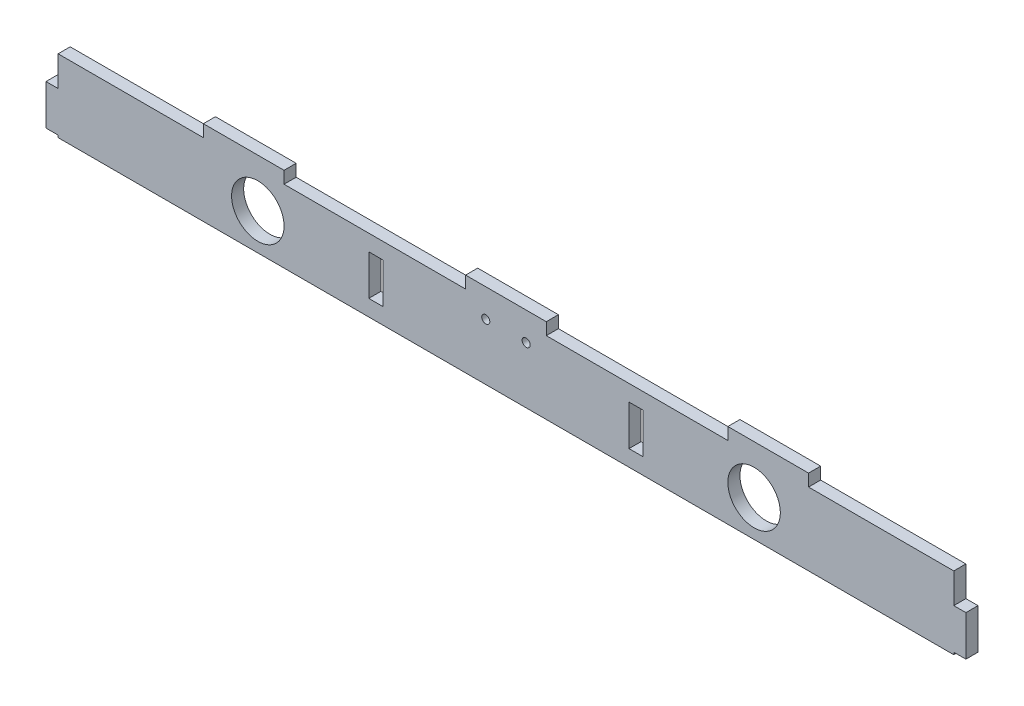
SolidWorks part; units mm, degrees
ref_plane "Alzado" through (0, 0, 0) normal (0, 0, 1) x (1, 0, 0)
ref_plane "Planta" through (0, 0, 0) normal (0, 1, 0) x (1, 0, 0)
ref_plane "Vista lateral" through (0, 0, 0) normal (1, 0, 0) x (0, 0, -1)
sketch "Croquis1" plane through (0, 0, 0) normal (0, 0, 1) x (1, 0, 0)
  line L0 (0, 0) -> (0, -9) construction
  line L1 (111, -9) -> (-111, -9)
  line L2 (111, -9) -> (111, 9)
  line L3 (111, 9) -> (-111, 9)
  line L4 (-111, -9) -> (-111, 9)
  line L5 (111, -9) -> (-111, 9) construction
  line L6 (111, 9) -> (-111, -9) construction
  line L7 (34, -5) -> (30.5, -5)
  line L8 (-34, 5) -> (-30.5, 5)
  line L9 (-34, 5) -> (-34, -5)
  line L10 (-34, -5) -> (-30.5, -5)
  line L11 (-30.5, 5) -> (-30.5, -5)
  line L12 (-34, 5) -> (-30.5, -5) construction
  line L13 (-34, -5) -> (-30.5, 5) construction
  line L14 (30.5, 5) -> (30.5, -5)
  line L15 (34, 5) -> (30.5, 5)
  line L16 (34, 5) -> (34, -5)
  line L17 (0, 0) -> (-111, 0) construction
  circle A1 centre (-5, 5) radius 1
  circle A3 centre (5, 5) radius 1
  circle A6 centre (-61.5, 0) radius 6.5
  circle A7 centre (61.5, 0) radius 6.5
  point P0 (0, 0)
  point P8 (-32.25, 0)
  dimension "D3" = 49.5
  dimension "D6" = 2
  dimension "D4" = 13
  dimension "D1" = 18
  dimension "D2" = 222
  dimension "D5" = 4
  dimension "D7" = 106
  dimension "D8" = 3.5
  dimension "D9" = 10
  dimension "D10" = 77
extrude "Saliente-Extruir1" add sketch "Croquis1" along normal blind 3
sketch "Croquis2" plane through (0, 9, 0) normal (0, 1, 0) x (1, 0, 0)
  line L0 (-55, 0) -> (-75, 0) construction
  line L1 (111, 0) -> (-111, 0) construction
  line L2 (75, 0) -> (55, 0) construction
  line L3 (-55, -3.325) -> (-55, 0.175) construction
  line L4 (-75, 0.175) -> (-75, -3.325) construction
  line L5 (-65, 0) -> (-65, -3) construction
  line L6 (111, -3) -> (-111, -3) construction
  line L7 (10, 0) -> (-10, 0) construction
  line L8 (-55, -3) -> (-75, -3)
  line L9 (-55, -3) -> (-55, 0)
  line L10 (-55, 0) -> (-75, 0)
  line L11 (-75, -3) -> (-75, 0)
  line L12 (-55, -3) -> (-75, 0) construction
  line L13 (-55, 0) -> (-75, -3) construction
  line L14 (55, 0.175) -> (55, -3.325) construction
  line L15 (-10, 0.175) -> (-10, -3.325) construction
  line L16 (10, -3.325) -> (10, 0.175) construction
  line L17 (0, 0) -> (0, -3) construction
  line L18 (75, -3.325) -> (75, 0.175) construction
  line L19 (65, 0) -> (65, -3) construction
  line L20 (10, -3) -> (-10, -3)
  line L21 (10, -3) -> (10, 0)
  line L22 (10, 0) -> (-10, 0)
  line L23 (-10, -3) -> (-10, 0)
  line L24 (10, -3) -> (-10, 0) construction
  line L25 (10, 0) -> (-10, -3) construction
  line L27 (75, -3) -> (55, -3)
  line L28 (75, -3) -> (75, 0)
  line L29 (75, 0) -> (55, 0)
  line L30 (55, -3) -> (55, 0)
  line L31 (75, -3) -> (55, 0) construction
  line L32 (75, 0) -> (55, -3) construction
  point P4 (-65, -1.5)
  point P17 (0, -1.5)
  point P28 (65, -1.5)
extrude "Saliente-Extruir2" add sketch "Croquis2" along normal blind 3
sketch "Croquis3" plane through (111, 0, 0) normal (1, 0, 0) x (0, 0, -1)
  line L0 (0, -8.45) -> (0, 1.55) construction
  line L1 (0, -9) -> (0, 9) construction
  line L2 (0.25, 1.55) -> (-3.25, 1.55) construction
  line L3 (-3.25, -8.45) -> (0.25, -8.45) construction
  line L4 (0, -3.45) -> (-3, -3.45) construction
  line L5 (-3, -9) -> (-3, 9) construction
  line L7 (-3, -8.45) -> (0, -8.45)
  line L8 (-3, -8.45) -> (-3, 1.55)
  line L9 (-3, 1.55) -> (0, 1.55)
  line L10 (0, -8.45) -> (0, 1.55)
  line L11 (-3, -8.45) -> (0, 1.55) construction
  line L12 (-3, 1.55) -> (0, -8.45) construction
  point P4 (-1.5, -3.45)
extrude "Saliente-Extruir3" add sketch "Croquis3" along normal blind 3
mirror "Simetría1" about plane through (0, 0, 0) normal (1, 0, 0) of "Saliente-Extruir3"
